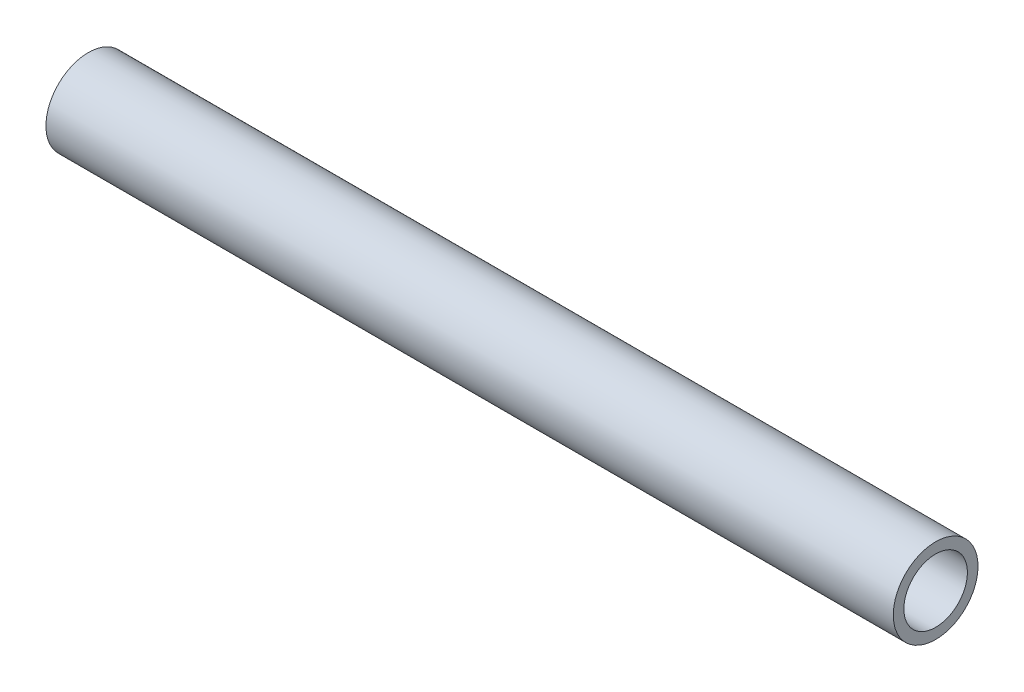
SolidWorks part; units mm, degrees
ref_plane "Front" through (0, 0, 0) normal (0, 0, 1) x (1, 0, 0)
ref_plane "Top" through (0, 0, 0) normal (0, 1, 0) x (1, 0, 0)
ref_plane "Right" through (0, 0, 0) normal (1, 0, 0) x (0, 0, -1)
sketch "Sketch1" plane through (0, 0, 0) normal (1, 0, 0) x (0, 0, -1)
  line L0 (9.525, 0) -> (12.7, 0) construction
  line L1 (9.525, 0) -> (12.7, 0) construction
  line L2 (11.1125, 0) -> (11.1125, 1.0672) construction
  circle A0 centre (0, 0) radius 12.7
  circle A1 centre (0, 0) radius 9.525
  point P4 (12.7, 0)
  point P5 (9.525, 0)
  dimension "OD" = 25.4
  dimension "ID" = 19.05
  dimension "Wall Thickness" = 3.175
sketch "Sketch2" plane through (0, 0, 0) normal (0, 0, 1) x (1, 0, 0)
  line L0 (-127, 0) -> (127, 0) construction
  point P2 (-95.25, 0)
  point P3 (95.25, 0)
  dimension "D1" = 31.75
  dimension "D2" = 31.75
sketch "Sketch3" plane through (0, 0, 0) normal (1, 0, 0) x (0, 0, -1)
  circle A0 centre (0, 0) radius 9.525 construction
  circle A1 centre (0, 0) radius 12.7 construction
  circle A2 centre (0, 0) radius 9.525
  circle A3 centre (0, 0) radius 12.7
extrude "Boss-Extrude1" add sketch "Sketch3" along normal mid plane 254
equation "\"D1@Boss-Extrude1\"=\"Length@Sketch2\""
equation "\"D1@Sketch2\"=\"OD@Sketch1\"*1.25"
equation "\"D2@Sketch2\"=\"D1@Sketch2\""
